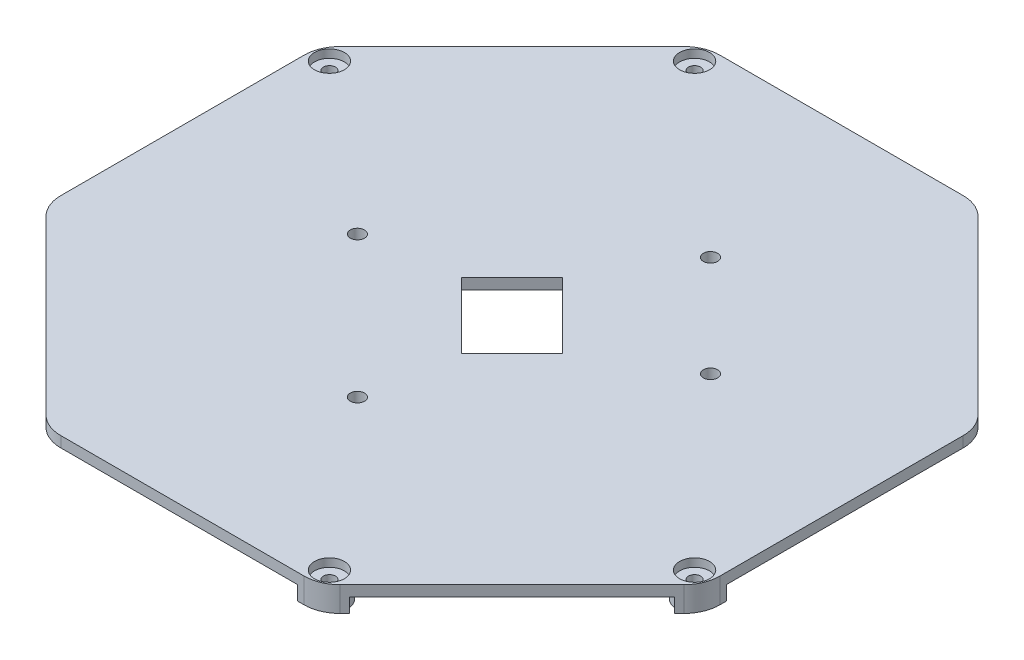
SolidWorks part; units mm, degrees
ref_plane "Front Plane" through (0, 0, 0) normal (0, 0, 1) x (1, 0, 0)
ref_plane "Top Plane" through (0, 0, 0) normal (0, 1, 0) x (1, 0, 0)
ref_plane "Right Plane" through (0, 0, 0) normal (1, 0, 0) x (0, 0, -1)
sketch "Sketch1" plane through (0, 0, 0) normal (0, 1, 0) x (1, 0, 0)
  line L7 (92.388, -38.2683) -> (92.388, 38.2683)
  line L8 (92.388, 38.2683) -> (38.2683, 92.388)
  line L9 (38.2683, 92.388) -> (-38.2683, 92.388)
  line L10 (-38.2683, 92.388) -> (-92.388, 38.2683)
  line L11 (-92.388, 38.2683) -> (-92.388, -38.2683)
  line L12 (-92.388, -38.2683) -> (-38.2683, -92.388)
  line L13 (-38.2683, -92.388) -> (38.2683, -92.388)
  line L14 (38.2683, -92.388) -> (92.388, -38.2683)
  circle A0 centre (0, 0) radius 92.388 construction
  dimension "D1" = 200
sketch "Sketch2" plane through (0, 0, 0) normal (0, 0, 1) x (1, 0, 0)
  line L0 (0, 0) -> (0, 3)
  dimension "D1" = 3
extrude "Boss-Extrude1" add sketch "Sketch1" along normal up to vertex (3 mm away) contours L13 L14 L7 L8 L9 L10 L11 L12 up to point (0, 3, 0)
sketch "Sketch13" plane through (0, 3, 0) normal (0, 1, 0) x (1, 0, 0)
  line L0 (-86.6808, 41.147) -> (-88.0951, 42.5612)
  line L1 (-88.0951, 42.5612) -> (-92.388, 38.2683)
  line L10 (-92.388, 38.2683) -> (-92.388, 32.1973)
  line L11 (-92.388, 32.1973) -> (-90.388, 32.1973)
  line L12 (-41.147, 86.6808) -> (-42.5612, 88.0951)
  line L13 (-42.5612, 88.0951) -> (-38.2683, 92.388)
  line L14 (-38.2683, 92.388) -> (-32.1973, 92.388)
  line L15 (-85.6948, 42.9894) -> (-88.0951, 45.3897) construction
  line L16 (-88.0951, 45.3897) -> (-94.388, 39.0968) construction
  line L17 (-32.1973, 90.388) -> (-32.1973, 92.388)
  line L23 (90.388, -32.1973) -> (92.388, -32.1973)
  line L24 (92.388, -32.1973) -> (92.388, -38.2683)
  line L25 (92.388, -38.2683) -> (88.0951, -42.5612)
  line L26 (-94.388, 39.0968) -> (-94.388, 30.1973) construction
  line L27 (-94.388, 30.1973) -> (-90.9935, 30.1973) construction
  line L28 (86.6808, -41.147) -> (88.0951, -42.5612)
  line L29 (32.1973, -90.388) -> (32.1973, -92.388)
  line L30 (32.1973, -92.388) -> (38.2683, -92.388)
  line L31 (38.2683, -92.388) -> (42.5612, -88.0951)
  line L32 (-30.1973, 90.9935) -> (-30.1973, 94.388) construction
  line L33 (41.147, -86.6808) -> (42.5612, -88.0951)
  line L34 (-39.0968, 94.388) -> (-30.1973, 94.388) construction
  line L35 (-45.3897, 88.0951) -> (-39.0968, 94.388) construction
  line L36 (-42.9894, 85.6948) -> (-45.3897, 88.0951) construction
  line L37 (85.6948, -42.9894) -> (88.0951, -45.3897) construction
  line L38 (94.388, -39.0968) -> (88.0951, -45.3897) construction
  line L39 (94.388, -30.1973) -> (94.388, -39.0968) construction
  line L40 (90.9935, -30.1973) -> (94.388, -30.1973) construction
  line L41 (30.1973, -90.9935) -> (30.1973, -94.388) construction
  line L42 (30.1973, -94.388) -> (39.0968, -94.388) construction
  line L43 (39.0968, -94.388) -> (45.3897, -88.0951) construction
  line L44 (42.9894, -85.6948) -> (45.3897, -88.0951) construction
  line L45 (-38.2683, 92.388) -> (38.2683, -92.388) construction
  line L46 (38.2683, -92.388) -> (39.3997, -94.085)
  line L48 (92.388, -38.2683) -> (-92.388, 38.2683) construction
  arc A15 (-90.9935, 30.1973) -> (-85.6948, 42.9894) centre (-87.388, 36.1973) ccw construction
  arc A16 (41.147, -86.6808) -> (32.1973, -90.388) centre (36.1973, -87.388) ccw
  arc A17 (90.388, -32.1973) -> (86.6808, -41.147) centre (87.388, -36.1973) ccw
  arc A18 (-41.147, 86.6808) -> (-32.1973, 90.388) centre (-36.1973, 87.388) ccw
  arc A19 (-90.388, 32.1973) -> (-86.6808, 41.147) centre (-87.388, 36.1973) ccw
  arc A20 (-42.9894, 85.6948) -> (-30.1973, 90.9935) centre (-36.1973, 87.388) ccw construction
  arc A21 (90.9935, -30.1973) -> (85.6948, -42.9894) centre (87.388, -36.1973) ccw construction
  arc A22 (42.9894, -85.6948) -> (30.1973, -90.9935) centre (36.1973, -87.388) ccw construction
  line M19 (-38.2683, -92.388) -> (38.2683, -92.388)
  line M20 (38.2683, -92.388) -> (92.388, -38.2683)
  line M21 (92.388, -38.2683) -> (92.388, 38.2683)
  line M24 (-38.2683, 92.388) -> (-92.388, 38.2683)
  line M25 (-92.388, 38.2683) -> (-92.388, -38.2683)
extrude "Boss-Extrude3" add sketch "Sketch13" against normal blind 7 contours L11 A19 L0 M24 M25 | L23 A17 L28 M20 M21 | L33 A16 L29 M19 M20 | A18 L17 L14 L13 L12
sketch "Sketch14" plane through (0, 3, 0) normal (0, 1, 0) x (1, 0, 0)
  point P0 (-87.388, 36.1973)
  point P1 (-36.1973, 87.388)
  point P3 (36.1973, -87.388)
  point P5 (87.388, -36.1973)
sketch "Sketch16" plane through (0, 0, 0) normal (0, -1, 0) x (1, 0, 0)
  line L0 (65.3281, 65.3281) -> (-65.3281, -65.3281)
  line L1 (42.5612, 88.0951) -> (88.0951, 42.5612) construction
  line L2 (-42.5612, -88.0951) -> (-88.0951, -42.5612) construction
  dimension "D1" = 184.7759
sketch "Sketch17" plane through (0, 3, 0) normal (0, -1, 0) x (1, 0, 0)
  point P0 (36.1973, 87.388)
  point P1 (87.388, 36.1973)
  point P3 (-36.1973, -87.388)
  point P5 (-87.388, -36.1973)
hole_wizard "CBORE for M3 Hex Head Machine Screw1" positions "Sketch17" profile "Sketch18" counterbore size "M3" standard "ANSI Metric" end condition through all
sketch "Sketch18" plane through (36.1973, 3, 87.388) normal (1, 0, 0) x (0, 0, 1)
  line L0 (0, 0) -> (0, 7)
  line L1 (0, 7) -> (1.7, 7)
  line L3 (1.7, 7) -> (1.7, 2.3)
  line L4 (1.7, 2.3) -> (4.2, 2.3)
  line L5 (4.2, 2.3) -> (4.2, 0)
  line L7 (4.2, 0) -> (0, 0)
  line L11 (0, -6.35) -> (0, 107.95) construction
  dimension "Thru Hole Dia." = 3.4
  dimension "Thru Hole Depth" = 7
  dimension "C'Bore Dia." = 8.4
  dimension "C'Bore Depth" = 2.3
sketch "Sketch19" plane through (0, 0, 92.388) normal (0, 0, 1) x (1, 0, 0)
  line L0 (-38.2683, 3) -> (-38.2683, 0) construction
ref_plane "Plane2" through (0, 1.5, 0) normal (0, 1, 0) x (1, 0, 0)
sketch "Sketch20" plane through (0, 3, 0) normal (0, 1, 0) x (1, 0, 0)
  line L1 (92.388, 38.2683) -> (-92.388, -38.2683) construction
  line L2 (-38.2683, 92.388) -> (38.2683, -92.388) construction
fillet "Fillet1" radius 10 8 edges at (38.2683, 1.5, -92.388) (92.388, 1.5, -38.2683) (92.388, -0.5, 38.2683) (-92.388, 1.5, 38.2683) (-92.388, -0.5, -38.2683) (-38.2683, -0.5, -92.388) (-38.2683, 1.5, 92.388) (38.2683, -0.5, 92.388)
sketch "Sketch22" plane through (0, 3, 0) normal (0, 1, 0) x (1, 0, 0)
  line L5 (65.3281, 65.3281) -> (-65.3281, -65.3281) construction
  line L6 (89.459, 41.1973) -> (41.1973, 89.459) construction
  line L10 (-89.459, -41.1973) -> (-41.1973, -89.459) construction
  line B0 (45.5023, 45.5023) -> (-25.2084, -25.2084) construction
  line B1 (20.7536, 70.2511) -> (70.2511, 20.7536) construction
  line B2 (20.7536, 70.2511) -> (-49.9571, -0.4596) construction
  line B3 (-49.9571, -0.4596) -> (-0.4596, -49.9571) construction
  line B4 (70.2511, 20.7536) -> (-0.4596, -49.9571) construction
  line B5 (5.4137, 90.2547) -> (90.2547, 5.4137)
  line B6 (47.8342, 47.8342) -> (-33.1971, -33.1971) construction
  circle B7 centre (13.6825, 41.9668) radius 4
  circle B8 centre (-41.4718, -1.8738) radius 4
  circle B9 centre (41.9668, 13.6825) radius 4
  circle B10 centre (-1.8738, -41.4718) radius 4
  dimension "D1" = 0
  dimension "D2" = 10.35
sketch_block_instance "Block1-1"
sketch_block "Block1" parameters "D4"=8, "D5"=8, "D1"=70, "D2"=100, "D3"=21, "D6"=114.5956, "D7"=70, "D8"=40, "D9"=56, "D10"=29, "D11"=3.2978
sketch "Sketch23" plane through (0, 3, 0) normal (0, 1, 0) x (1, 0, 0)
  circle A0 centre (-41.4718, -1.8738) radius 4 construction
  circle A1 centre (-1.8738, -41.4718) radius 4 construction
  circle A2 centre (41.9668, 13.6825) radius 4 construction
  circle A3 centre (13.6825, 41.9668) radius 4 construction
  circle A4 centre (-41.4718, -1.8738) radius 4 construction
  circle A5 centre (-1.8738, -41.4718) radius 4 construction
  circle A6 centre (41.9668, 13.6825) radius 4 construction
  circle A7 centre (13.6825, 41.9668) radius 4 construction
  circle A8 centre (-41.4718, -1.8738) radius 2
  circle A9 centre (13.6825, 41.9668) radius 2
  circle A10 centre (41.9668, 13.6825) radius 2
  circle A11 centre (-1.8738, -41.4718) radius 2
  dimension "D1" = 2
extrude "Cut-Extrude1" cut sketch "Sketch23" against normal through all
sketch "Sketch24" plane through (0, 3, 0) normal (0, 1, 0) x (1, 0, 0)
  line L0 (-16.2635, 2.1213) -> (-2.1213, 16.2635)
  line L1 (-2.1213, 16.2635) -> (16.2635, -2.1213)
  line L2 (16.2635, -2.1213) -> (2.1213, -16.2635)
  line L3 (2.1213, -16.2635) -> (-16.2635, 2.1213)
  line L4 (-2.1213, 16.2635) -> (2.1213, -16.2635) construction
  line L6 (-41.1973, 89.459) -> (-89.459, 41.1973) construction
  line L7 (-89.459, -41.1973) -> (-41.1973, -89.459) construction
  line L9 (89.459, 41.1973) -> (41.1973, 89.459) construction
  line L10 (-49.9571, -0.4596) -> (-0.4596, -49.9571) construction
  point P2 (0, 0)
  dimension "D1" = 26
  dimension "D2" = 20
extrude "Cut-Extrude2" cut sketch "Sketch24" against normal through all
equation "\"across_flat\"= 200"
equation "\"D1@Sketch1\"=\"across_flat\""
equation "\"motor_groove\"= 43"
equation "\"thickness_1\"= 3"
equation "\"thickness_2\"=2"
equation "\"battery_holder_height\"= 20"
equation "\"gen_allowance\"= 10"
equation "\"motor_width\"= 60"
equation "\"castor_breadth\"= 46 - 10"
equation "\"castor_length\"= 52 - 10"
equation "\"castor_groove\"= 8"
equation "\"ultrasonic_groove\"= 14"
equation "\"fillet1\"=3"
equation "\"hole_height\"=8"
equation "\"D1@Boss-Extrude3\"=\"hole_height\" - 1"
equation "\"space\"= 10"
equation "\"D1@Sketch2\"=\"thickness_1\""
